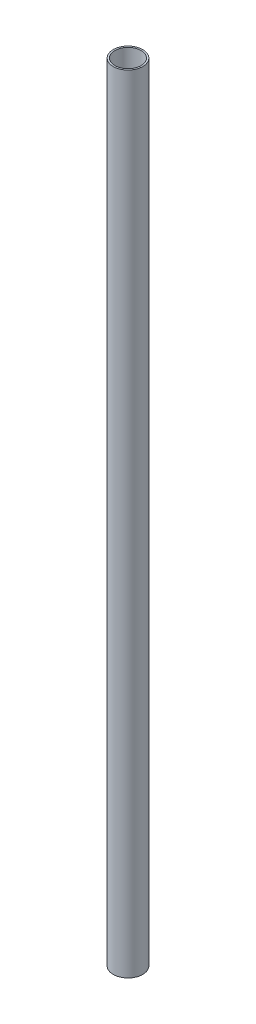
SolidWorks part; units mm, degrees
ref_plane "Front Plane" through (0, 0, 0) normal (0, 0, 1) x (1, 0, 0)
ref_plane "Top Plane" through (0, 0, 0) normal (0, 1, 0) x (1, 0, 0)
ref_plane "Right Plane" through (0, 0, 0) normal (1, 0, 0) x (0, 0, -1)
sketch "Sketch1" plane through (0, 0, 0) normal (0, 1, 0) x (1, 0, 0)
  circle A0 centre (0, 0) radius 22.5
  dimension "D1" = 45
extrude "Boss-Extrude1" add sketch "Sketch1" along normal blind 1200 contours A0
sketch "Sketch2" plane through (0, 1200, 0) normal (0, 1, 0) x (1, 0, 0)
  circle A0 centre (0, 0) radius 20
  dimension "D1" = 40
extrude "Cut-Extrude1" cut sketch "Sketch2" against normal through all contours A0
